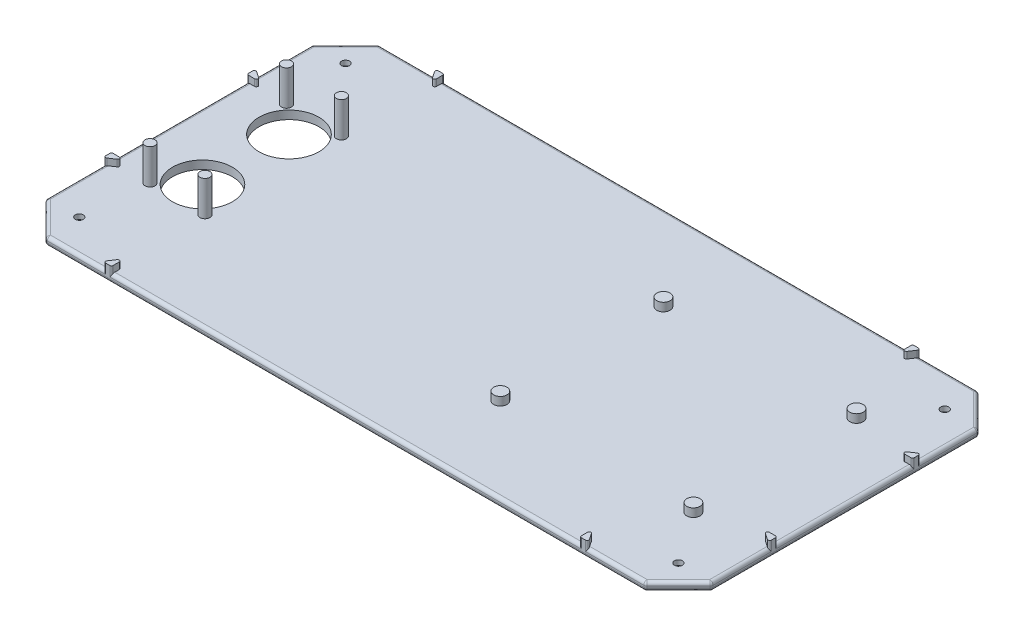
SolidWorks part; units mm, degrees
ref_plane "Front Plane" through (0, 0, 0) normal (0, 0, 1) x (1, 0, 0)
ref_plane "Top Plane" through (0, 0, 0) normal (0, 1, 0) x (1, 0, 0)
ref_plane "Right Plane" through (0, 0, 0) normal (1, 0, 0) x (0, 0, -1)
sketch "Sketch1" plane through (0, 0, 0) normal (0, 1, 0) x (1, 0, 0)
  line L0 (-42.8795, -50) -> (-18.9309, -50) construction
  line L1 (10, 0) -> (190, 0)
  line L2 (0, -10) -> (0, -90)
  line L3 (10, -100) -> (190, -100)
  line L4 (200, -10) -> (200, -90)
  line L5 (100, -119.9176) -> (100, -112.0024) construction
  line L6 (0, -10) -> (10, 0)
  line L7 (0, -90) -> (10, -100)
  line L8 (190, -100) -> (200, -90)
  line L9 (190, 0) -> (200, -10)
  point P0 (0, 0)
  point P1 (200, -100)
  point P2 (0, -100)
  point P3 (200, 0)
  dimension "D1" = 200
  dimension "D2" = 100
extrude "Boss-Extrude1" add sketch "Sketch1" along normal blind 2.5
hole_wizard "CSK for M2 Flat Head Machine Screw1" positions "Sketch4" profile "Sketch5" countersink size "M2" standard "ANSI Metric" end condition through all
sketch "Sketch4" plane through (0, 0, 0) normal (0, -1, 0) x (-1, 0, 0)
  line L6 (-200, -90) -> (-200, -10) construction
  line L10 (-190, 0) -> (-10, 0) construction
  line L11 (0, -10) -> (0, -90) construction
  line L12 (-10, -100) -> (-190, -100) construction
  point P6 (-190, -10)
  point P72 (-190, -90)
  point P85 (-10, -10)
  point P87 (-10, -90)
  dimension "D1" = 10
  dimension "D2" = 10
  dimension "D7" = 10
  dimension "D8" = 10
  dimension "D13" = 10
  dimension "D14" = 10
  dimension "D15" = 10
  dimension "D16" = 10
sketch "Sketch5" plane through (190, 0, 10) normal (1, 0, 0) x (0, 0, -1)
  line L0 (0, 0) -> (0, 2.5)
  line L1 (0, 2.5) -> (1.2, 2.5)
  line L2 (1.2, 2.5) -> (1.2, 1)
  line L3 (1.2, 1) -> (2.2, 0)
  line L5 (2.2, 0) -> (0, 0)
  line L6 (-1.2, 1) -> (-2.2, 0) construction
  line L11 (0, -6.35) -> (0, 107.95) construction
  dimension "Thru Hole Dia." = 2.4
  dimension "Thru Hole Depth" = 2.5
  dimension "Near C'Sink Dia." = 4.4
  dimension "Near C'Sink Angle" = 90
sketch "Sketch6" plane through (0, 2.5, 0) normal (0, 1, 0) x (1, 0, 0)
  line L0 (-21.5814, -50) -> (-48.7277, -50) construction
  line L1 (0, -10) -> (0, -90) construction
  line L2 (20, -29.8417) -> (20, -59.4239) construction
  circle A0 centre (11.75, -29.5) radius 1.5
  circle A1 centre (11.75, -70.5) radius 1.5
  circle A2 centre (28.25, -70.5) radius 1.5
  circle A3 centre (28.25, -29.5) radius 1.5
  point P4 (0, -50)
  dimension "D1" = 3
  dimension "D4" = 20
  dimension "D2" = 8.25
  dimension "D3" = 20.5
extrude "Boss-Extrude2" add sketch "Sketch6" along normal blind 10.5 contours A0
sketch "Sketch7" plane through (0, 2.5, 0) normal (0, 1, 0) x (1, 0, 0)
  circle A0 centre (20, -37) radius 8 construction
  circle A1 centre (20, -63) radius 8 construction
  circle A2 centre (20, -37) radius 8 construction
  circle A3 centre (20, -63) radius 8 construction
  circle A4 centre (20, -37) radius 9
  circle A5 centre (20, -63) radius 9
  dimension "D1" = 1
extrude "Cut-Extrude1" cut sketch "Sketch7" against normal blind 10.5
sketch "Sketch8" plane through (0, 2.5, 0) normal (0, 1, 0) x (1, 0, 0)
  line L0 (-33.755, -50) -> (-59.5799, -50) construction
  line L1 (0, -10) -> (0, -90) construction
  line L2 (150, -10.5345) -> (150, -57.0223) construction
  circle A0 centre (121, -25.5) radius 2
  circle A2 centre (121, -74.5) radius 2
  circle A3 centre (179, -74.5) radius 2
  circle A4 centre (179, -25.5) radius 2
  point P4 (0, -50)
  dimension "D1" = 4
  dimension "D3" = 29
  dimension "D2" = 24.5
  dimension "D4" = 150
extrude "Boss-Extrude3" add sketch "Sketch8" along normal blind 2.5
sketch "Sketch9" plane through (0, 2.5, 0) normal (0, 1, 0) x (1, 0, 0)
  line L0 (170.3333, -96) -> (173, -100)
  line L1 (170.3359, -96.0038) -> (172.4063, -99.1094) construction
  line L2 (10, -100) -> (190, -100) construction
  line L3 (196, -70.3333) -> (200, -73)
  line L4 (196.0038, -70.3359) -> (199.1094, -72.4063) construction
  line L5 (200, -90) -> (200, -10) construction
  line L6 (170.3333, -96) -> (170.3333, -100)
  line L7 (170.3333, -100) -> (173, -100)
  line L8 (196, -70.3333) -> (200, -70.3333)
  line L9 (200, -70.3333) -> (200, -73)
  line L10 (100, 11.6834) -> (100, -9.8073) construction
  line L11 (190, 0) -> (10, 0) construction
  line L12 (11.5355, -50) -> (-45.3054, -50) construction
  line L13 (0, -10) -> (0, -90) construction
  line L14 (0, -70.3333) -> (0, -73)
  line L15 (4, -70.3333) -> (0, -70.3333)
  line L16 (29.6667, -100) -> (27, -100)
  line L17 (29.6667, -96) -> (29.6667, -100)
  line L18 (4, -70.3333) -> (0, -73)
  line L19 (29.6667, -96) -> (27, -100)
  line L20 (29.6667, -4) -> (27, 0)
  line L21 (4, -29.6667) -> (0, -27)
  line L22 (29.6667, -4) -> (29.6667, 0)
  line L23 (29.6667, 0) -> (27, 0)
  line L24 (4, -29.6667) -> (0, -29.6667)
  line L25 (0, -29.6667) -> (0, -27)
  line L26 (200, -29.6667) -> (200, -27)
  line L27 (196, -29.6667) -> (200, -29.6667)
  line L28 (170.3333, 0) -> (173, 0)
  line L29 (170.3333, -4) -> (170.3333, 0)
  line L30 (196, -29.6667) -> (200, -27)
  line L31 (170.3333, -4) -> (173, 0)
  point P18 (100, 0)
  point P23 (0, -50)
  dimension "D1" = 4
  dimension "D2" = 4
extrude "Boss-Extrude4" add sketch "Sketch9" along normal blind 2
fillet "Fillet1" radius 1 32 edges at (5, 2.5, 95) (5, 0, 95) (181.5, 2.5, 100) (18.5, 2.5, 100) (100, 0, 100) (195, 2.5, 95) (195, 0, 95) (200, 2.5, 18.5) (200, 2.5, 81.5) (200, 0, 50) (195, 2.5, 5) (195, 0, 5) (0, 0, 50) (0, 2.5, 18.5) (0, 2.5, 81.5) (100, 0, 0) (18.5, 2.5, 0) (181.5, 2.5, 0) (5, 2.5, 5) (5, 0, 5) (0, 1.25, 10) (10, 1.25, 0) (200, 1.25, 10) (190, 1.25, 0) (200, 1.25, 90) (190, 1.25, 100) (10, 1.25, 100) (0, 1.25, 90) (200, 2.5, 50) (100, 2.5, 0) (0, 2.5, 50) (100, 2.5, 100)
fillet "Fillet2" radius 0.5 24 edges at (29.6667, 3.5, 96) (29.6667, 3, 100) (27, 3, 100) (4, 3.5, 70.3333) (0, 3, 73) (0, 3, 70.3333) (4, 3.5, 29.6667) (0, 3, 29.6667) (0, 3, 27) (29.6667, 3, 0) (27, 3, 0) (29.6667, 3.5, 4) (173, 3, 0) (170.3333, 3, 0) (170.3333, 3.5, 4) (196, 3.5, 29.6667) (200, 3, 27) (200, 3, 29.6667) (196, 3.5, 70.3333) (200, 3, 70.3333) (200, 3, 73) (170.3333, 3.5, 96) (170.3333, 3, 100) (173, 3, 100)
